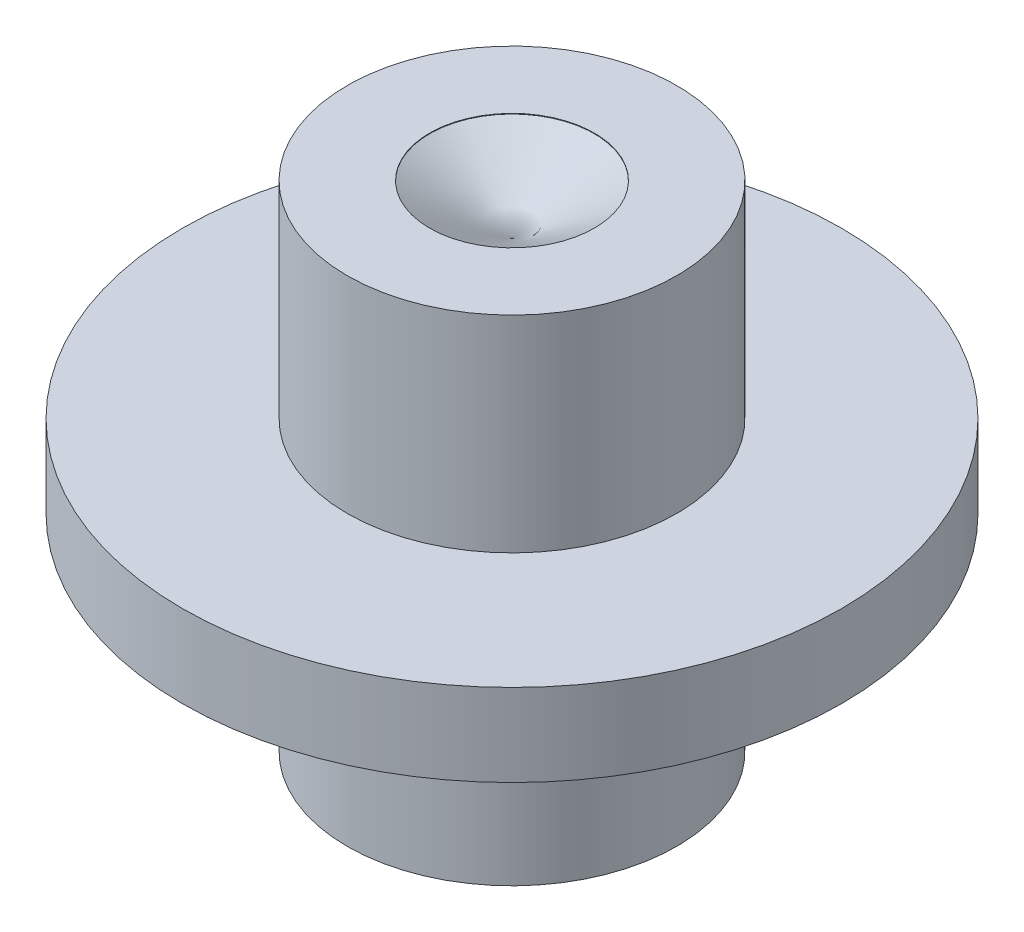
SolidWorks part; units mm, degrees
material "ALUMINUM 6061"
ref_plane "Front Plane" through (0, 0, 0) normal (0, 0, 1) x (1, 0, 0)
ref_plane "Top Plane" through (0, 0, 0) normal (0, 1, 0) x (1, 0, 0)
ref_plane "Right Plane" through (0, 0, 0) normal (1, 0, 0) x (0, 0, -1)
sketch "Sketch1" plane through (0, 0, 0) normal (0, 0, 1) x (1, 0, 0)
  line L0 (0, 4.7625) -> (3.175, 4.7625)
  line L1 (3.175, 4.7625) -> (3.175, 0.7938)
  line L2 (3.175, 0.7938) -> (6.35, 0.7937)
  line L3 (6.35, 0.7937) -> (6.35, -0.7937)
  line L4 (6.35, -0.7937) -> (3.175, -0.7938)
  line L5 (3.175, -0.7938) -> (3.175, -4.7625)
  line L6 (3.175, -4.7625) -> (0, -4.7625)
  line L7 (0, 4.7625) -> (0, -4.7625) construction
  line L8 (0, 4.7625) -> (0, -4.7625)
  dimension "D1" = 3.175
  dimension "D2" = 9.525
  dimension "D3" = 1.5875
  dimension "D4" = 6.35
revolve "Revolve1" add sketch "Sketch1" angle 360 about L7
hole_wizard "1/8 (0.125) Diameter Hole1" positions "Sketch3" profile "Sketch5" hole size "1/8" standard "ANSI Inch"
sketch "Sketch3" plane through (0, 4.7625, 0) normal (0, 1, 0) x (1, 0, 0)
  point P0 (0, 0)
sketch "Sketch5" plane through (0, 4.7625, 0) normal (1, 0, 0) x (0, 0, 1)
  line L0 (0, 0) -> (0, 0.9652)
  line L1 (0, 0.9652) -> (1.5875, 0.0113)
  line L2 (1.5875, 0.0113) -> (1.5875, 0)
  line L5 (1.5875, 0) -> (0, 0)
  line L10 (0, 0.9652) -> (-1.5875, 0.0113) construction
  line L11 (0, -6.35) -> (0, 107.95) construction
  dimension "Hole Dia." = 3.175
  dimension "Hole Depth" = 0.9652
  dimension "Drill Angle" = 118
move or copy body "Body-Move/Copy1" [suppressed] bodies to move or copy 101
